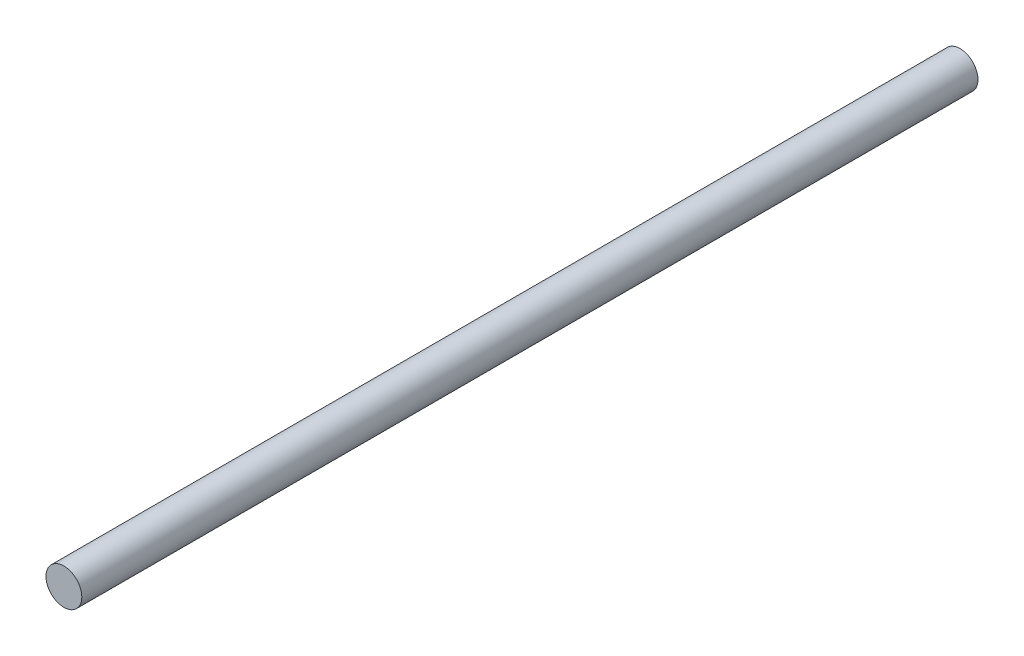
SolidWorks part; units mm, degrees
ref_plane "前视基准面" through (0, 0, 0) normal (0, 0, 1) x (1, 0, 0)
ref_plane "上视基准面" through (0, 0, 0) normal (0, 1, 0) x (1, 0, 0)
ref_plane "右视基准面" through (0, 0, 0) normal (1, 0, 0) x (0, 0, -1)
sketch "草图1" plane through (0, 0, 0) normal (0, 0, 1) x (1, 0, 0)
  circle A0 centre (0, 0) radius 5
  dimension "D1" = 10
extrude "凸台-拉伸1" add sketch "草图1" along normal blind 250
cosmetic thread "装饰螺纹线1" parameters "D2"=8
cosmetic thread "装饰螺纹线2" parameters "D2"=8
